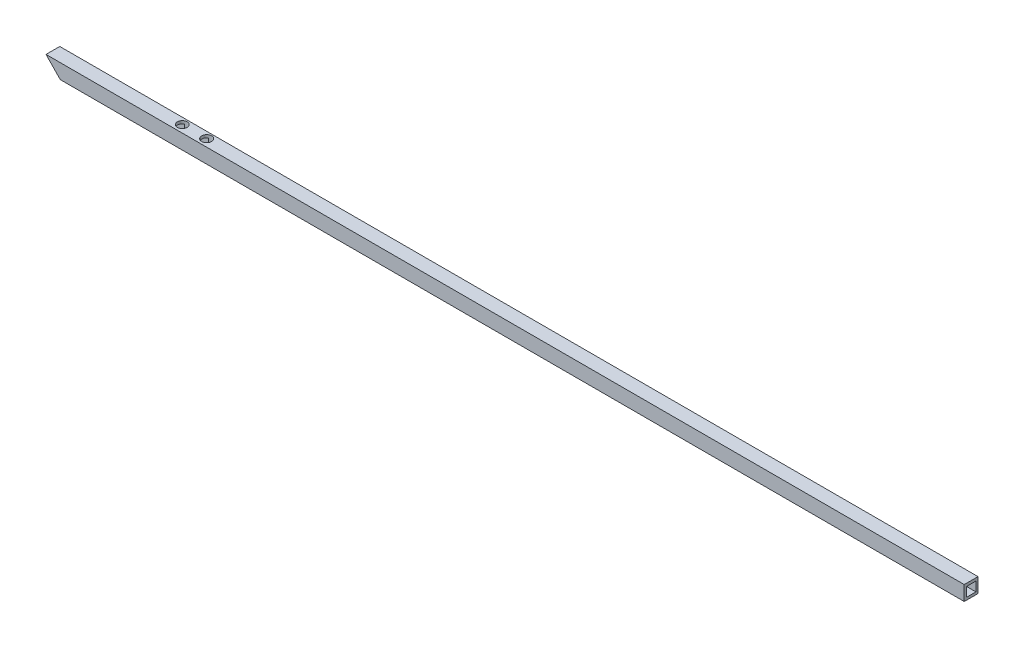
SolidWorks part; units mm, degrees
material "1060 Alloy"
ref_plane "Front Plane" through (0, 0, 0) normal (0, 0, 1) x (1, 0, 0)
ref_plane "Top Plane" through (0, 0, 0) normal (0, 1, 0) x (1, 0, 0)
ref_plane "Right Plane" through (0, 0, 0) normal (1, 0, 0) x (0, 0, -1)
sketch "Sketch1" plane through (0, 0, 0) normal (0, 0, 1) x (1, 0, 0)
  line L0 (-69.9612, 0) -> (438.0388, 0)
  line L2 (438.0388, -8.1455) -> (-62.0553, -8.1455)
  line L3 (-62.0553, -8.1455) -> (-69.9612, 0)
  line L4 (438.0388, 0) -> (438.0388, -8.1455)
extrude "Boss-Extrude1" add sketch "Sketch1" along normal blind 7.62
sketch "Sketch3" plane through (438.0388, 0, 0) normal (1, 0, 0) x (0, 0, -1)
  line L1 (-6.3274, -1.5552) -> (-1.1629, -1.5552)
  line L2 (-6.3274, -1.5552) -> (-6.3274, -6.7337)
  line L3 (-6.3274, -6.7337) -> (-1.1629, -6.7337)
  line L4 (-1.1629, -1.5552) -> (-1.1629, -6.7337)
extrude "Cut-Extrude2" cut sketch "Sketch3" against normal through all
sketch "Sketch4" plane through (0, 0, 0) normal (0, 1, 0) x (1, 0, 0)
  circle A0 centre (1.3675, -3.5463) radius 2.6954
  circle A1 centre (14.8576, -3.5463) radius 2.7478
extrude "Cut-Extrude3" cut sketch "Sketch4" against normal blind 5.08
sketch "Sketch5" plane through (0, -8.1455, 0) normal (0, -1, 0) x (1, 0, 0)
  circle A0 centre (355.6421, 4.3455) radius 2.2746
  circle A1 centre (368.0186, 4.3455) radius 2.3553
extrude "Cut-Extrude4" cut sketch "Sketch5" against normal blind 5.08
